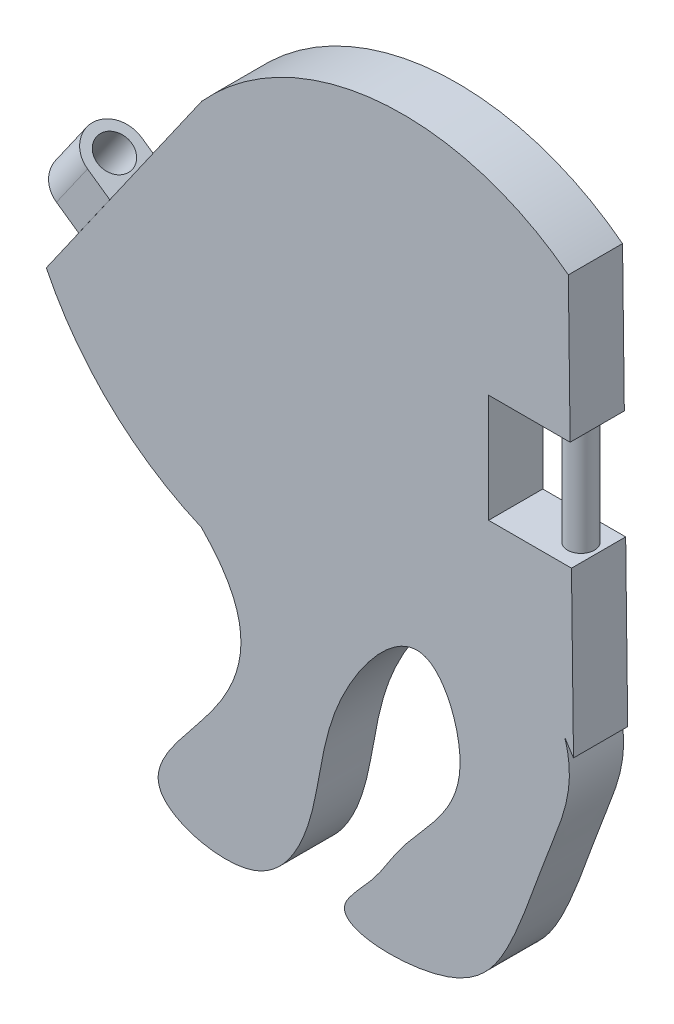
SolidWorks part; units mm, degrees
ref_plane "Alzado" through (0, 0, 0) normal (0, 0, 1) x (1, 0, 0)
ref_plane "Planta" through (0, 0, 0) normal (0, 1, 0) x (1, 0, 0)
ref_plane "Vista lateral" through (0, 0, 0) normal (1, 0, 0) x (0, 0, -1)
sketch "Croquis1" plane through (0, 0, 0) normal (0, 0, 1) x (1, 0, 0)
  line L1 (-40.22, 0) -> (0, 0) construction
  line L2 (-40.1771, 40.8737) -> (-57.3844, 16.2991)
  line L3 (0, 0) -> (1.5832, -2.4246)
  line L4 (1.5832, -2.4246) -> (1.5832, 43.5754)
  line L5 (-57.3844, 16.2991) -> (1.5832, 16.2991) construction
  line L6 (-40.1771, 40.8737) -> (1.5832, 40.8737) construction
  arc A1 (-57.3844, 16.2991) -> (-40.22, 0) centre (-26.8542, 31.2627) ccw
  arc A2 (-40.1771, 40.8737) -> (1.5832, 43.5754) centre (-17.9089, 20.7707) cw
  spline S0 degree 3 poles (0, 0) (1.4204, -4.2998) (-1.9076, -11.4466) (-5.2573, -22.1052) (-10.8415, -31.173) (-27.9498, -30.8509) (-20.7431, -24.1498) (-17.4737, -17.8417) (-9.0621, -11.3741) (-15.3909, 5.224) (-27.7722, -10.7108) (-26.6871, -21.67) (-33.871, -32.3365) (-49.7114, -28.3238) (-35.2745, -14.5918) (-34.2016, -6.0586) (-40.22, 0) knots 0 0 0 0 0.07758 0.150369 0.212574 0.288439 0.319302 0.356974 0.436636 0.500261 0.583217 0.683911 0.736106 0.804521 0.878414 1 1 1 1
  point P4 (0, 0)
  point P14 (0, 0)
  point P16 (0, -6.8852)
  point P20 (3.0139, 0)
  point P22 (3.1586, -3.0191)
  point P24 (3.0398, -2.187)
  point P26 (3.9336, -2.3677)
  point P28 (3.1221, -2.6996)
  point P30 (3.0778, 0.1997)
  point P32 (8.8974, 1.2267)
  point P34 (1.5832, -2.4246)
  dimension "D2" = 30
  dimension "D5" = 30
  dimension "D6" = 34
  dimension "D1" = 46
  dimension "D3" = 30
  dimension "D4" = 55
extrude "Saliente-Extruir1" add sketch "Croquis1" along normal blind 6
ref_plane "Plano1" through (-46.1636, 32.3241, 0) normal (-0.8192, 0.5736, 0) x (0, 0, 1)
ref_plane "Plano2" through (21.0745, 30.0974, 0) normal (0.5736, 0.8192, 0) x (0.8192, -0.5736, 0)
sketch "Croquis4" plane through (21.0745, 30.0974, 0) normal (0.5736, 0.8192, 0) x (0.8192, -0.5736, 0)
  line L1 (-56.3553, 3.3) -> (-56.3553, -3.3) construction
  line L2 (-59.3553, -6.0337) -> (-56.3553, -6.0337)
  line L4 (-59.3553, -0.0337) -> (-56.3553, -0.0337)
  line L5 (-56.3553, -6.0337) -> (-56.3553, -0.0337)
  arc A0 (-59.3553, -0.0337) -> (-59.3553, -6.0337) centre (-59.3553, -3.0337) ccw
  dimension "D1" = 6
  dimension "D2" = 3
  dimension "D3" = 0
extrude "Saliente-Extruir3" add sketch "Croquis4" along normal blind 6 from offset 50 separate body offset against normal yes
sketch "Croquis6" plane through (-4.1629, -5.9453, 0) normal (0.5736, 0.8192, 0) x (0.8192, -0.5736, 0)
  line L0 (-59.3553, -6.0337) -> (-56.3553, -6.0337) construction
  circle A0 centre (-59.3828, -3.0337) radius 1.9
  dimension "D1" = 3.8
  dimension "D2" = 3
extrude "Cortar-Extruir1" cut sketch "Croquis6" against normal blind 6
sketch "Croquis7" plane through (0, 0, 6) normal (0, 0, 1) x (1, 0, 0)
  line L0 (1.5832, -2.4246) -> (1.5832, 43.5754) construction
  line L1 (1.5832, 28.5754) -> (-8.4168, 28.5754)
  line L2 (1.5832, 28.5754) -> (1.5832, 16.5754)
  line L3 (1.5832, 16.5754) -> (-8.4168, 16.5754)
  line L4 (-8.4168, 28.5754) -> (-8.4168, 16.5754)
  line L5 (1.5832, -2.4246) -> (-57.6471, -2.4246) construction
  dimension "D1" = 10
  dimension "D2" = 12
  dimension "D3" = 19
extrude "Cortar-Extruir2" cut sketch "Croquis7" against normal blind 6
sketch "Croquis8" plane through (0, 28.5754, 0) normal (0, -1, 0) x (1, 0, 0)
  line L0 (1.5832, 6) -> (-8.4168, 6) construction
  circle A0 centre (-1.1844, 3) radius 1.5
  dimension "D1" = 3
  dimension "D2" = 3
extrude "Saliente-Extruir4" add sketch "Croquis8" along normal up to next
sketch "Croquis9" plane through (0, 0, 6) normal (0, 0, 1) x (1, 0, 0)
  line L0 (1.813, -4.0168) -> (0.1948, 52.1795)
  line L1 (0.1948, 52.1795) -> (3.7644, 52.1795)
  line L2 (3.7644, 52.1795) -> (5.3826, -4.0168)
  line L3 (5.3826, -4.0168) -> (1.813, -4.0168)
  point P2 (0, 0)
extrude "Cortar-Extruir3" cut sketch "Croquis9" against normal blind 10
sketch "Croquis10" plane through (0, 0, 6) normal (0, 0, 1) x (1, 0, 0)
  line L0 (0.4153, 44.5241) -> (1.0147, -3.8661)
  line L1 (0.4153, 44.5241) -> (0.8745, 28.5754) construction
  line L2 (1.0147, -3.8661) -> (7.9233, -3.8661)
  line L3 (7.9233, -3.8661) -> (7.9233, 44.5241)
  line L4 (7.9233, 44.5241) -> (0.4153, 44.5241)
  arc A0 (0.4153, 44.5241) -> (-40.1771, 40.8737) centre (-17.9089, 20.7707) ccw construction
extrude "Cortar-Extruir4" cut sketch "Croquis10" against normal blind 10
